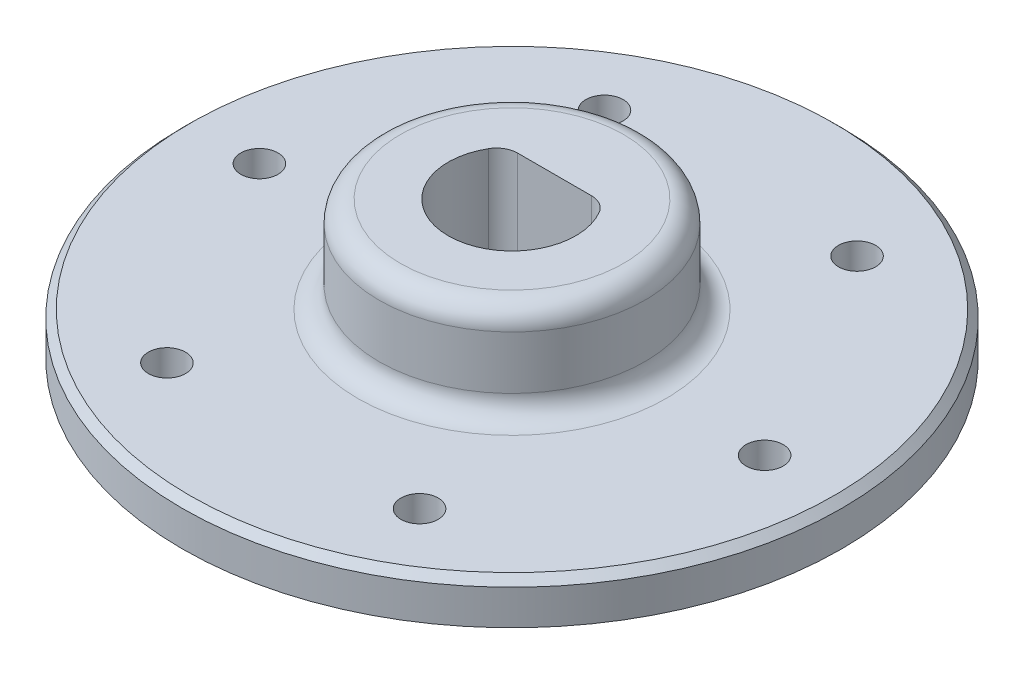
SolidWorks part; units mm, degrees
material "Cast Alloy Steel"
ref_plane "Front" through (0, 0, 0) normal (0, 0, 1) x (1, 0, 0)
ref_plane "Top" through (0, 0, 0) normal (0, 1, 0) x (1, 0, 0)
ref_plane "Right" through (0, 0, 0) normal (1, 0, 0) x (0, 0, -1)
sketch "Sketch1" plane through (0, 0, 0) normal (0, 1, 0) x (1, 0, 0)
  line L0 (0, 0) -> (0, 23.75) construction
  line L1 (0, 0) -> (-11.875, 20.5681) construction
  circle A7 centre (0, 0) radius 31
  circle A9 centre (0, 0) radius 23.75 construction
  circle A10 centre (-11.875, 20.5681) radius 1.75
  circle A11 centre (11.875, 20.5681) radius 1.75
  circle A12 centre (23.75, 0) radius 1.75
  circle A13 centre (11.875, -20.5681) radius 1.75
  circle A14 centre (-11.875, -20.5681) radius 1.75
  circle A15 centre (-23.75, 0) radius 1.75
  point P19 (0, 0)
  dimension "D1" = 47.5
  dimension "D2" = 30
  dimension "D4" = 62
  dimension "D3" = 3.5
extrude "Boss-Extrude1" add sketch "Sketch1" along normal blind 4
sketch "Sketch2" plane through (0, 4, 0) normal (0, 1, 0) x (1, 0, 0)
  circle A0 centre (0, 0) radius 12.5
  dimension "D1" = 25
extrude "Boss-Extrude2" add sketch "Sketch2" along normal blind 9
fillet "Fillet2" radius 2 2 edges at (0, 4, 12.5) (0, 13, 12.5)
sketch "Sketch4" plane through (0, 13, 0) normal (0, 1, 0) x (1, 0, 0)
  line L0 (0, 0) -> (0, 12.5) construction
  circle A0 centre (0, 0) radius 12.5 construction
ref_plane "Plane1" through (0, 13, -12.5) normal (0, 0, -1) x (-1, 0, 0)
chamfer "Chamfer2" distance 0.7 angle 45 1 edges at (0, 4, 31)
sketch "Sketch6" plane through (0, 0, 0) normal (0, -1, 0) x (-1, 0, 0)
  circle A0 centre (0, 0) radius 11.5
  dimension "D1" = 23
extrude "Boss-Extrude3" add sketch "Sketch6" along normal blind 9
fillet "Fillet3" radius 2 1 edges at (0, -9, -11.5)
sketch "Sketch7" plane through (0, -9, 0) normal (0, -1, 0) x (-1, 0, 0)
  line L0 (4.4721, 4) -> (-4.4721, 4)
  arc A0 (-4.4721, 4) -> (4.4721, 4) centre (0, 0) ccw
  dimension "D1" = 12
  dimension "D2" = 4
extrude "Cut-Extrude3" cut sketch "Sketch7" against normal through all
fillet "Fillet4" radius 2 2 edges at (-4.4721, 2, -4) (4.4721, 2, -4)
